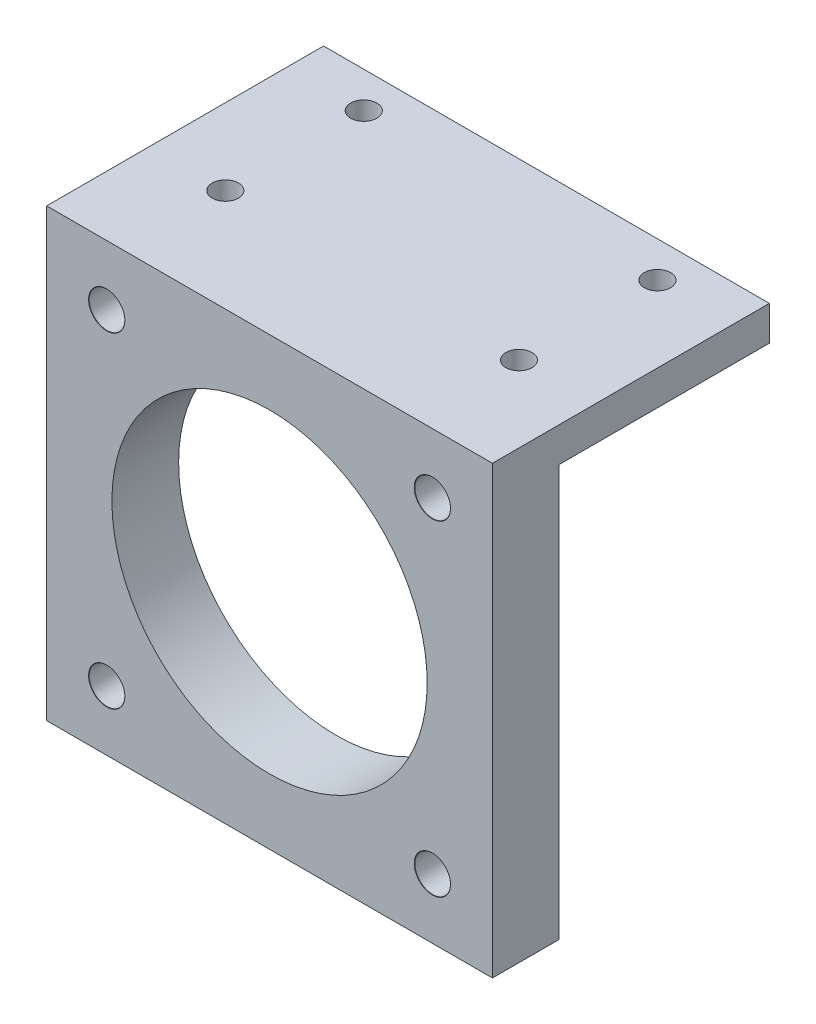
SolidWorks part; units mm, degrees
material "6061 Alloy"
ref_plane "Front Plane" through (0, 0, 0) normal (0, 0, 1) x (1, 0, 0)
ref_plane "Top Plane" through (0, 0, 0) normal (0, 1, 0) x (1, 0, 0)
ref_plane "Right Plane" through (0, 0, 0) normal (1, 0, 0) x (0, 0, -1)
sketch "Sketch1" plane through (0, 0, 0) normal (0, 1, 0) x (1, 0, 0)
  line L0 (-21.209, 10) -> (-13.9706, 6.5871)
  line L1 (-21.209, -10) -> (21.209, -10)
  line L2 (-21.209, -10) -> (-21.209, 10)
  line L3 (-21.209, 10) -> (21.209, 10)
  line L4 (21.209, -10) -> (21.209, 10)
  line L5 (-21.209, -10) -> (21.209, 10) construction
  line L6 (-21.209, 10) -> (21.209, -10) construction
  line L7 (21.209, 10) -> (13.9706, 6.5871)
  line L8 (-21.209, -10) -> (-13.9706, -6.5871)
  line L9 (21.209, -10) -> (13.9706, -6.5871)
  point P0 (0, 0)
extrude "Boss-Extrude1" add sketch "Sketch1" along normal blind 6.35
hole_wizard "Tap Drill for M3x0.5 Tap2" positions "Sketch4" profile "Sketch5" hole size "M3x0.5" standard "ANSI Metric"
sketch "Sketch4" plane through (0, 0, 0) normal (0, -1, 0) x (-1, 0, 0)
  point P0 (-13.9706, 6.5871)
  point P3 (-13.9706, -6.5871)
  point P6 (13.9706, 6.5871)
  point P9 (13.9706, -6.5871)
sketch "Sketch5" plane through (13.9706, 0, -6.5871) normal (1, 0, 0) x (0, 0, -1)
  line L0 (0, 0) -> (0, 10)
  line L1 (0, 10) -> (1.25, 9.2489)
  line L2 (1.25, 9.2489) -> (1.25, 0.025)
  line L3 (1.25, 0.025) -> (1.275, 0)
  line L5 (1.275, 0) -> (0, 0)
  line L6 (-1.25, 0.025) -> (-1.275, 0) construction
  line L10 (0, 10) -> (-1.25, 9.2489) construction
  line L11 (0, -6.35) -> (0, 107.95) construction
  dimension "Hole Dia." = 2.5
  dimension "Hole Depth" = 10
  dimension "Near C'Sink Dia." = 2.55
  dimension "Near C'Sink Angle" = 90
  dimension "Drill Angle" = 118
sketch "Sketch12" plane through (0, 0, 10) normal (0, 0, 1) x (1, 0, 0)
  line L1 (-21.209, 6.35) -> (21.209, 6.35)
  line L2 (-21.209, 6.35) -> (-21.209, 0)
  line L3 (-21.209, 0) -> (21.209, 0)
  line L4 (21.209, 6.35) -> (21.209, 0)
extrude "Boss-Extrude2" add sketch "Sketch12" along normal blind 6.35
sketch "Sketch13" plane through (0, 0, 0) normal (0, -1, 0) x (1, 0, 0)
  line L0 (21.209, 16.35) -> (21.209, -10) construction
  line L1 (-21.209, 16.35) -> (21.209, 16.35)
  line L2 (-21.209, 16.35) -> (-21.209, 10)
  line L3 (-21.209, 10) -> (21.209, 10)
  line L4 (21.209, 16.35) -> (21.209, 10)
extrude "Boss-Extrude3" add sketch "Sketch13" along normal blind 36.068
sketch "Sketch14" plane through (0, 0, 16.35) normal (0, 0, 1) x (1, 0, 0)
  line L0 (21.209, 6.35) -> (15.494, 6.35)
  line L1 (21.209, 6.35) -> (-21.209, 6.35) construction
  line L2 (-21.209, 6.35) -> (-15.494, 6.35)
  line L3 (-15.494, 6.35) -> (-15.494, 0.635)
  line L4 (15.494, 6.35) -> (15.494, 0.635)
  line L5 (-21.209, -36.068) -> (-15.494, -36.068)
  line L6 (21.209, -36.068) -> (-21.209, -36.068) construction
  line L7 (-15.494, -36.068) -> (-15.494, -30.353)
  line L8 (21.209, -36.068) -> (15.494, -36.068)
  line L9 (15.494, -36.068) -> (15.494, -30.353)
hole_wizard "M3 Clearance Hole1" positions "Sketch15" profile "Sketch16" hole size "M3" standard "ANSI Metric" end condition through all
sketch "Sketch15" plane through (0, 0, 16.35) normal (0, 0, 1) x (1, 0, 0)
  point P0 (-15.494, 0.635)
  point P3 (15.494, 0.635)
  point P6 (15.494, -30.353)
  point P9 (-15.494, -30.353)
sketch "Sketch16" plane through (-15.494, 0.635, 16.35) normal (1, 0, 0) x (0, -1, 0)
  line L0 (0, 0) -> (0, 26.35)
  line L1 (0, 26.35) -> (1.7, 26.35)
  line L2 (1.7, 26.35) -> (1.7, 0.025)
  line L3 (1.7, 0.025) -> (1.725, 0)
  line L5 (1.725, 0) -> (0, 0)
  line L6 (-1.7, 0.025) -> (-1.725, 0) construction
  line L11 (0, -6.35) -> (0, 107.95) construction
  dimension "Thru Hole Dia." = 3.4
  dimension "Thru Hole Depth" = 26.35
  dimension "Near C'Sink Dia." = 3.45
  dimension "Near C'Sink Angle" = 90
sketch "Sketch17" plane through (0, 0, 0) normal (0, -1, 0) x (1, 0, 0)
  line L1 (-21.209, 10) -> (21.209, 10)
  line L2 (-21.209, 10) -> (-21.209, -10)
  line L3 (-21.209, -10) -> (21.209, -10)
  line L4 (21.209, 10) -> (21.209, -10)
extrude "Cut-Extrude1" cut sketch "Sketch17" against normal blind 3.068
sketch "Sketch19" plane through (0, 0, 16.35) normal (0, 0, 1) x (1, 0, 0)
  circle A0 centre (0, -14.859) radius 15
extrude "Cut-Extrude2" cut sketch "Sketch19" against normal through all
